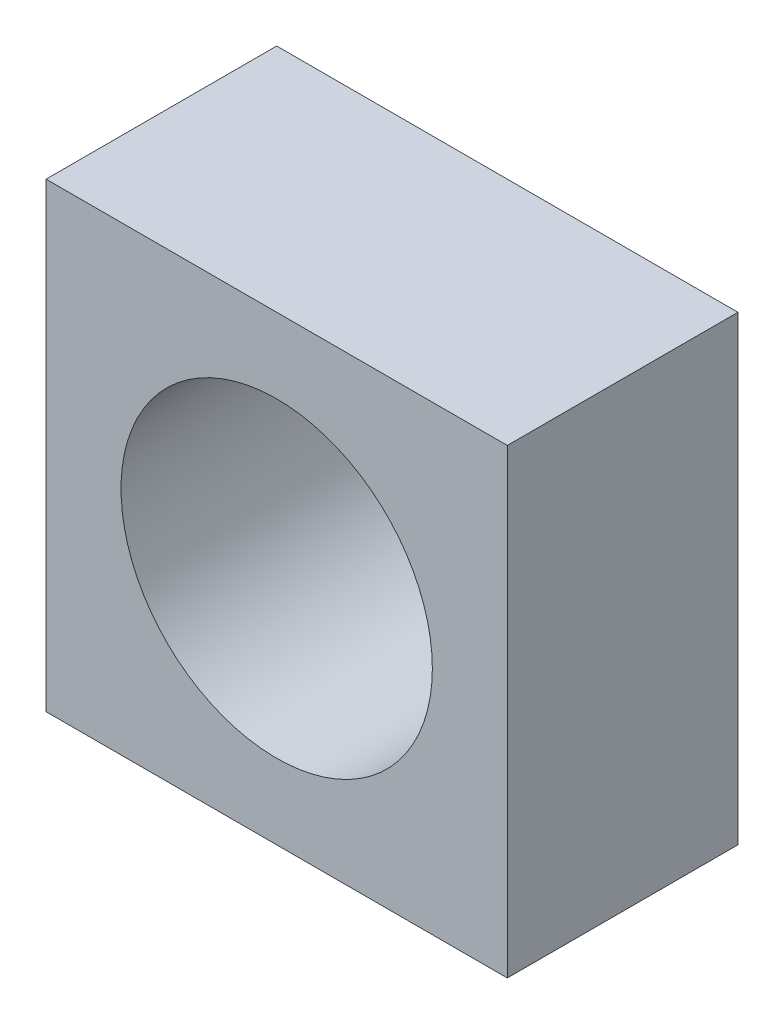
SolidWorks part; units mm, degrees
ref_plane "Front Plane" through (0, 0, 0) normal (0, 0, 1) x (1, 0, 0)
ref_plane "Top Plane" through (0, 0, 0) normal (0, 1, 0) x (1, 0, 0)
ref_plane "Right Plane" through (0, 0, 0) normal (1, 0, 0) x (0, 0, -1)
other "Configuration Table"
sketch "Sketch2" plane through (0, 0, 0) normal (0, 0, 1) x (1, 0, 0)
  line L1 (-4, -4) -> (4, -4)
  line L2 (-4, -4) -> (-4, 4)
  line L3 (-4, 4) -> (4, 4)
  line L4 (4, -4) -> (4, 4)
extrude "Reference_square_nut" add sketch "Sketch2" along normal blind 4 from offset 0
sketch "Sketch3" plane through (0, 0, 0) normal (0, 0, 1) x (1, 0, 0)
  circle A0 centre (0, 0) radius 2.7
extrude "Simplified_clearance_bore" cut sketch "Sketch3" along normal blind 4 from offset 0
